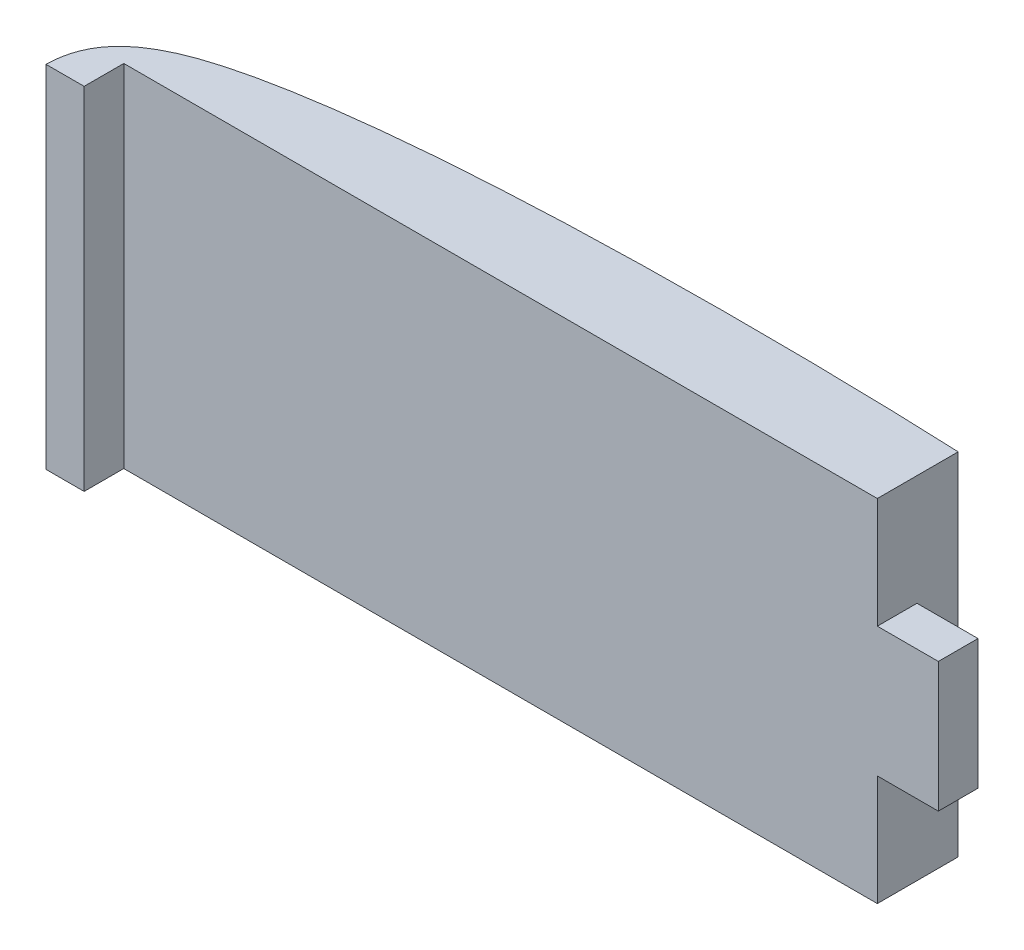
SolidWorks part; units mm, degrees
ref_plane "Спереди" through (0, 0, 0) normal (0, 0, 1) x (1, 0, 0)
ref_plane "Сверху" through (0, 0, 0) normal (0, 1, 0) x (1, 0, 0)
ref_plane "Справа" through (0, 0, 0) normal (1, 0, 0) x (0, 0, -1)
sketch "Эскиз1" plane through (0, 0, 0) normal (0, 1, 0) x (1, 0, 0)
  line L0 (0, 0) -> (0, 5.3)
  line L1 (0, 0) -> (-49.4, 0)
  line L2 (-49.4, 0) -> (-49.4, -2.6)
  line L3 (-49.4, -2.6) -> (-51.9, -2.6)
  line L4 (-44.183, 5.6) -> (0, 5.6) construction
  line L5 (-49.4, 0) -> (-49.4, 1.7) construction
  spline S0 degree 3 poles (0, 5.3) (-7.9939, 5.669) (-41.5732, 6.3726) (-51.8478, 0.9846) (-51.9, -2.6) knots 0 0 0 0 0.717431 1 1 1 1
  point P7 (-44.183, 3.5432)
  dimension "D1" = 5.6
  dimension "D2" = 5.3
  dimension "D3" = 49.4
  dimension "D4" = 2.5
  dimension "D5" = 2.6
  dimension "D6" = 1.7
extrude "Бобышка-Вытянуть1" add sketch "Эскиз1" along normal blind 23
sketch "Эскиз2" plane through (0, 0, 0) normal (1, 0, 0) x (0, 0, -1)
  line L0 (0, 23) -> (0, 0) construction
  line L4 (2.6, 7.25) -> (2.6, 15.75)
  line L5 (0, 11.5) -> (2.6, 15.75) construction
  line L6 (0, 11.5) -> (2.6, 7.25) construction
  line L7 (2.6, 15.75) -> (0, 15.75)
  line L8 (0, 15.75) -> (0, 7.25)
  line L9 (0, 7.25) -> (2.6, 7.25)
  point P0 (0, 11.5)
  dimension "D1" = 8.5
  dimension "D2" = 2.6
extrude "Бобышка-Вытянуть2" add sketch "Эскиз2" along normal blind 4
